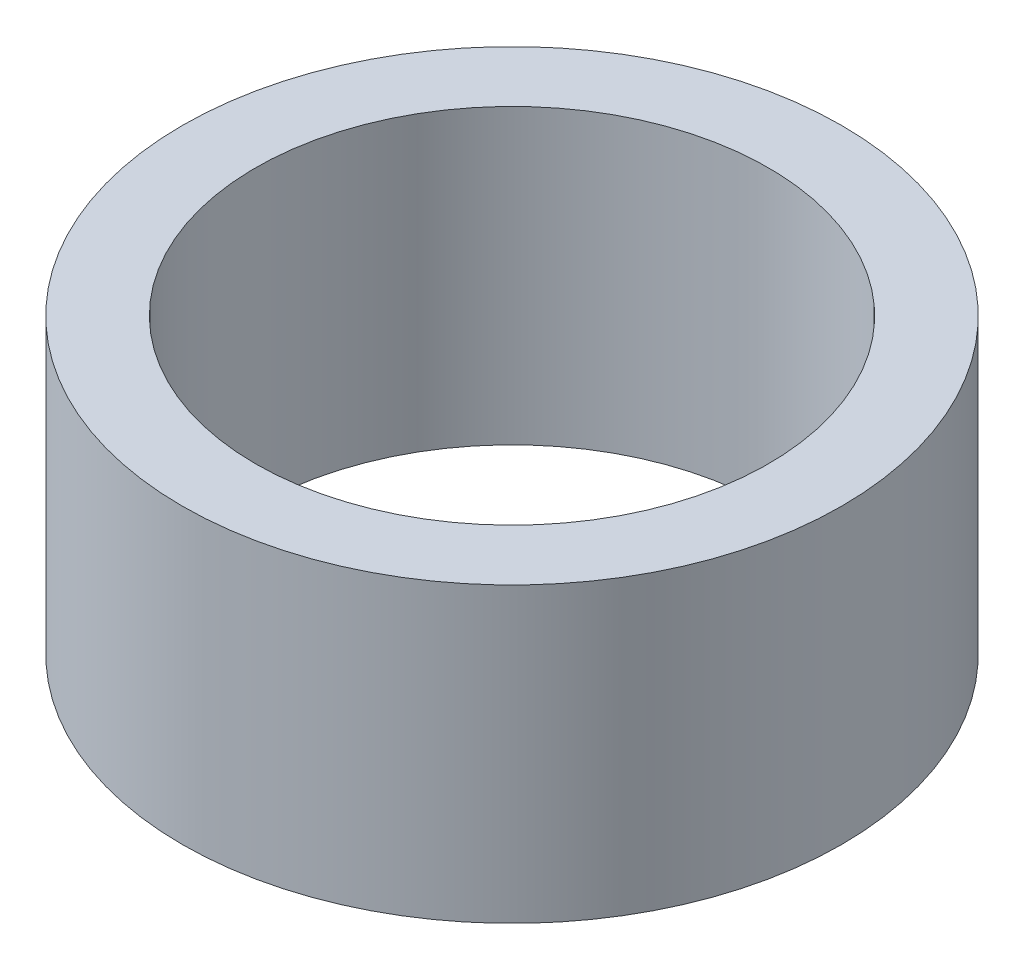
SolidWorks part; units mm, degrees
material "ASTM A36 Steel"
ref_plane "Front Plane" through (0, 0, 0) normal (0, 0, 1) x (1, 0, 0)
ref_plane "Top Plane" through (0, 0, 0) normal (0, 1, 0) x (1, 0, 0)
ref_plane "Right Plane" through (0, 0, 0) normal (1, 0, 0) x (0, 0, -1)
sketch "Sketch1" plane through (0, 0, 0) normal (0, 1, 0) x (1, 0, 0)
  circle A0 centre (0, 0) radius 28.575
  circle A1 centre (0, 0) radius 22.225
  dimension "D1" = 44.45
  dimension "D2" = 57.15
extrude "Boss-Extrude1" add sketch "Sketch1" along normal blind 25.4
